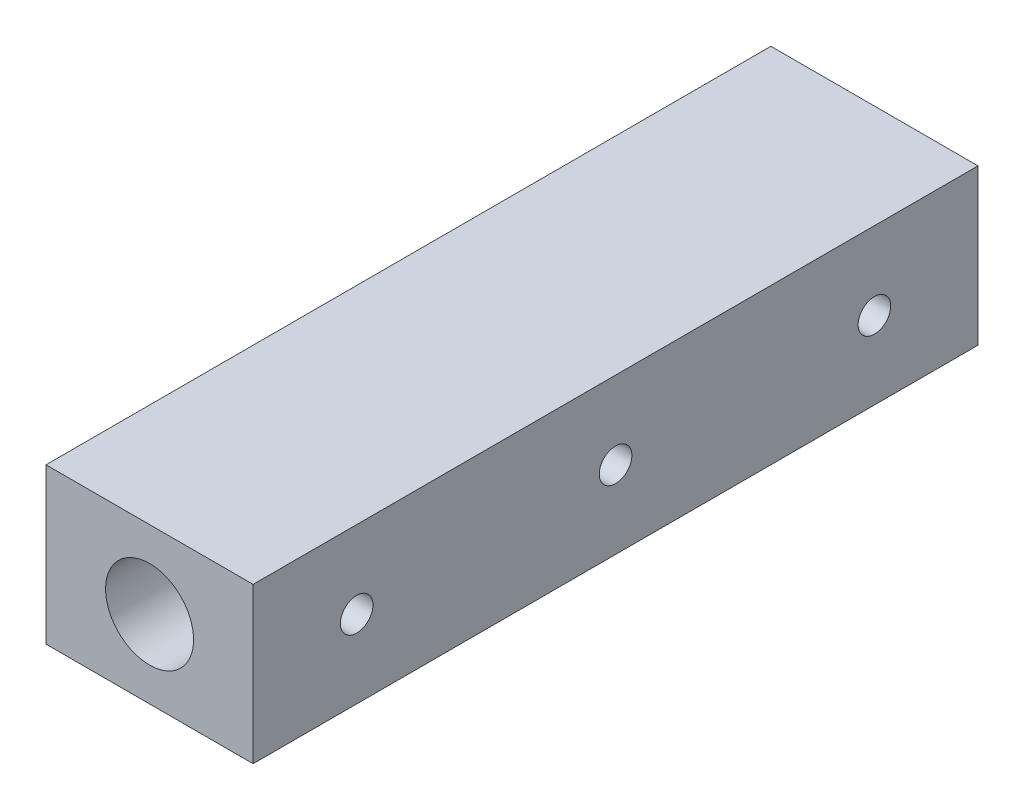
SolidWorks part; units mm, degrees
ref_plane "前视基准面" through (0, 0, 0) normal (0, 0, 1) x (1, 0, 0)
ref_plane "上视基准面" through (0, 0, 0) normal (0, 1, 0) x (1, 0, 0)
ref_plane "右视基准面" through (0, 0, 0) normal (1, 0, 0) x (0, 0, -1)
other "Configuration Table"
sketch "草图1" plane through (0, 0, 0) normal (0, 0, 1) x (1, 0, 0)
  line L1 (0, 0) -> (20, 0)
  line L2 (0, 0) -> (0, -15)
  line L3 (0, -15) -> (20, -15)
  line L4 (20, 0) -> (20, -15)
  dimension "D1" = 20
  dimension "D2" = 15
extrude "凸台-拉伸1" add sketch "草图1" along normal blind 70
sketch "草图2" plane through (0, 0, 0) normal (0, 0, -1) x (-1, 0, 0)
  line L0 (-10, 0) -> (-10, -15) construction
  line L1 (-20, 0) -> (0, 0) construction
  line L2 (0, -15) -> (-20, -15) construction
  circle A0 centre (-10, -7.5) radius 4.25
  dimension "D1" = 8.5
extrude "切除-拉伸1" cut sketch "草图2" against normal through all
sketch "草图3" plane through (20, 0, 0) normal (1, 0, 0) x (0, 0, -1)
  line L0 (-70, -7.5) -> (0, -7.5) construction
  line L1 (-70, -15) -> (-70, 0) construction
  line L2 (0, -15) -> (0, 0) construction
  circle A0 centre (-60, -7.5) radius 1.575
  circle A1 centre (-35, -7.5) radius 1.575
  circle A2 centre (-10, -7.5) radius 1.575
  dimension "D1" = 3.15
  dimension "D2" = 10
  dimension "D3" = 25
  dimension "D4" = 10
extrude "切除-拉伸2" cut sketch "草图3" against normal through all
